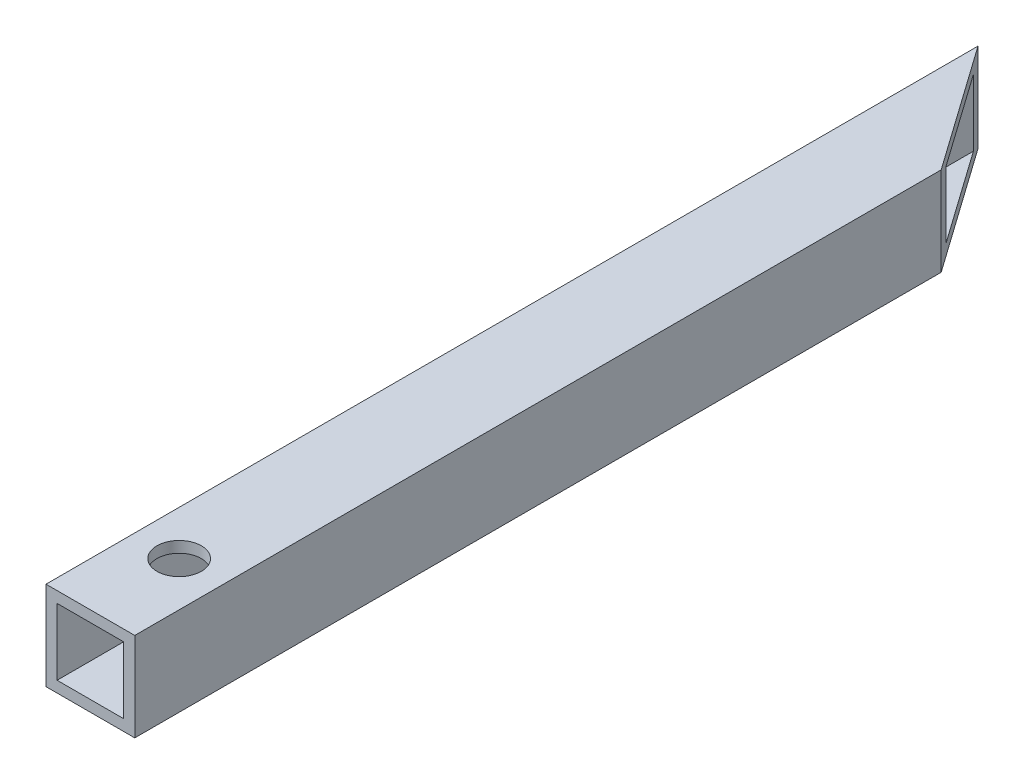
SolidWorks part; units mm, degrees
ref_plane "Front Plane" through (0, 0, 0) normal (0, 0, 1) x (1, 0, 0)
ref_plane "Top Plane" through (0, 0, 0) normal (0, 1, 0) x (1, 0, 0)
ref_plane "Right Plane" through (0, 0, 0) normal (1, 0, 0) x (0, 0, -1)
sketch "Sketch1" plane through (0, 0, 0) normal (0, 0, 1) x (1, 0, 0)
  line L0 (3.175, 22.225) -> (22.225, 22.225)
  line L1 (0, 0) -> (25.4, 0)
  line L2 (0, 0) -> (0, 25.4)
  line L3 (0, 25.4) -> (25.4, 25.4)
  line L4 (25.4, 0) -> (25.4, 25.4)
  line L5 (0, 0) -> (25.4, 25.4) construction
  line L6 (0, 25.4) -> (25.4, 0) construction
  line L7 (22.225, 3.175) -> (22.225, 22.225)
  line L8 (3.175, 3.175) -> (22.225, 3.175)
  line L9 (3.175, 3.175) -> (3.175, 22.225)
  point P4 (12.7, 12.7)
  dimension "D1" = 25.4
  dimension "D2" = 3.175
extrude "Boss-Extrude1" add sketch "Sketch1" along normal blind 266.7
sketch "Sketch2" plane through (0, 25.4, 0) normal (0, 1, 0) x (1, 0, 0)
  line L1 (25.4, -35.9382) -> (0, 0)
  line L2 (0, 0) -> (25.4, 0)
  line L3 (25.4, -266.7) -> (25.4, 0) construction
  line L4 (25.4, 0) -> (0, 0) construction
  line L5 (25.4, 0) -> (25.4, -35.9382)
extrude "Cut-Extrude1" cut sketch "Sketch2" against normal up to next
sketch "Sketch3" plane through (0, 25.4, 0) normal (0, 1, 0) x (1, 0, 0)
  line L0 (0, -241.3) -> (25.4, -241.3) construction
  line L1 (0, -266.7) -> (0, 0) construction
  line L2 (25.4, -266.7) -> (25.4, -35.9382) construction
  line L3 (12.7, -266.7) -> (12.7, -241.3) construction
  line L4 (25.4, -266.7) -> (0, -266.7) construction
  circle A0 centre (12.7, -241.3) radius 6.35
  dimension "D1" = 12.7
  dimension "D2" = 25.4
extrude "Cut-Extrude2" cut sketch "Sketch3" against normal through all
